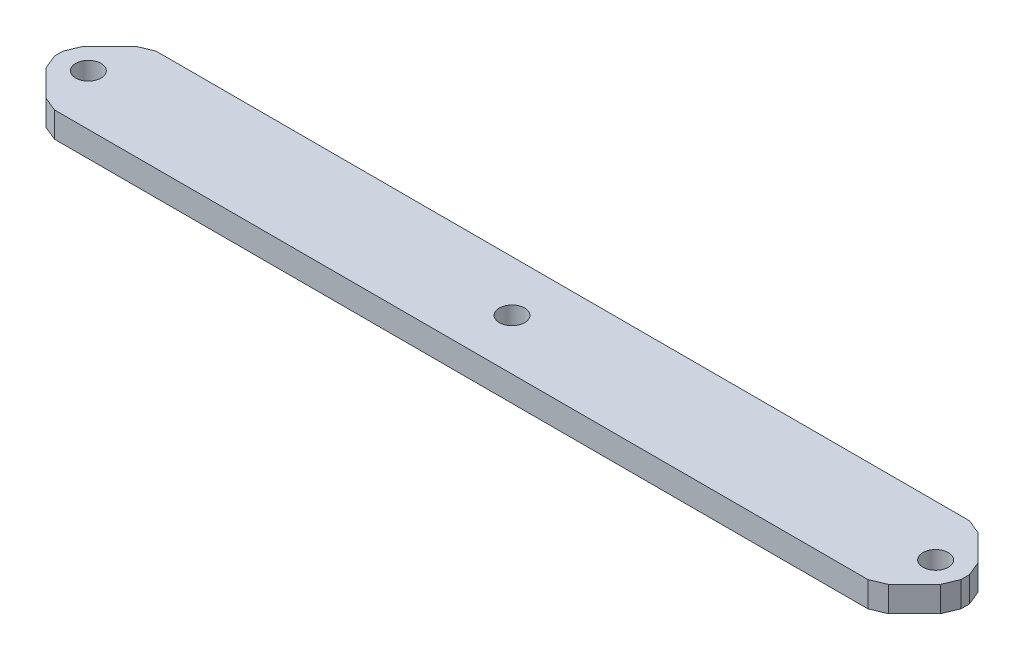
SolidWorks part; units mm, degrees
ref_plane "Front Plane" through (0, 0, 0) normal (0, 0, 1) x (1, 0, 0)
ref_plane "Top Plane" through (0, 0, 0) normal (0, 1, 0) x (1, 0, 0)
ref_plane "Right Plane" through (0, 0, 0) normal (1, 0, 0) x (0, 0, -1)
sketch "Sketch1" plane through (0, 0, 0) normal (0, 1, 0) x (1, 0, 0)
  line L0 (-55, 3) -> (-52, 6)
  line L1 (-52, 6) -> (52, 6)
  line L2 (-55, 3) -> (-55, -3)
  line L3 (-52, -6) -> (52, -6)
  line L4 (55, 3) -> (55, -3)
  line L5 (-55, 6) -> (55, -6) construction
  line L6 (-55, -6) -> (55, 6) construction
  line L7 (-55, -3) -> (-52, -6)
  line L8 (52, 6) -> (55, 3)
  line L9 (52, -6) -> (55, -3)
  circle A0 centre (-50, 0) radius 1.5
  circle A1 centre (0, 0) radius 1.5
  circle A2 centre (50, 0) radius 1.5
  point P0 (0, 0)
  dimension "D3" = 3
  dimension "D1" = 110
  dimension "D2" = 12
  dimension "D4" = 5
  dimension "D10" = 5
extrude "Boss-Extrude1" add sketch "Sketch1" along normal blind 3 contours A0 | L8 L4 L9 L3 L7 L2 L0 L1 | A1 | A2
sketch "Sketch2" plane through (0, 3, 0) normal (0, 1, 0) x (1, 0, 0)
  line L0 (-53.5, 4.5) -> (-53.5, -4.5)
  line L1 (-55, 3) -> (-52, 6) construction
  line L2 (-55, -3) -> (-52, -6) construction
  line L3 (-53.5, -4.5) -> (-55, -3)
  line L4 (-55, -3) -> (-55, 3)
  line L5 (-55, 3) -> (-53.5, 4.5)
  line L6 (0, 0) -> (0, 9.9984) construction
  line L7 (53.5, -4.5) -> (55, -3)
  line L8 (55, -3) -> (55, 3)
  line L9 (55, 3) -> (53.5, 4.5)
  line L10 (53.5, 4.5) -> (53.5, -4.5)
extrude "Cut-Extrude1" cut sketch "Sketch2" against normal through all both and the other way through all
sketch "Sketch3" plane through (0, 3, 0) normal (0, 1, 0) x (1, 0, 0)
  line L0 (-53.5, 1.5) -> (-49, 6)
  line L1 (-53.5, 4.5) -> (-53.5, -4.5) construction
  line L2 (-52, 6) -> (52, 6) construction
  line L3 (-53.5, 1.5) -> (-53.5, 4.5)
  line L4 (-53.5, 4.5) -> (-52, 6)
  line L5 (-52, 6) -> (-49, 6)
  line L6 (0, 0) -> (-7.5431, 0) construction
  line L7 (-2.9544, 6.0226) -> (-23.5602, -21.0219) construction
  line L8 (0, 0) -> (0, 4.5) construction
  line L9 (-53.5, -1.5) -> (-53.5, -4.5)
  line L10 (-53.5, -4.5) -> (-52, -6)
  line L11 (-52, -6) -> (-49, -6)
  line L12 (-53.5, -1.5) -> (-49, -6)
  line L13 (53.5, 1.5) -> (53.5, 4.5)
  line L14 (52, 6) -> (49, 6)
  line L15 (53.5, 4.5) -> (52, 6)
  line L16 (53.5, 1.5) -> (49, 6)
  line L17 (52, -6) -> (49, -6)
  line L18 (53.5, -4.5) -> (52, -6)
  line L19 (53.5, -1.5) -> (53.5, -4.5)
  line L20 (53.5, -1.5) -> (49, -6)
  line M11 (-52, 6) -> (-53.5, 4.5)
  line M12 (-53.5, 4.5) -> (-53.5, -4.5)
  line M13 (-53.5, -4.5) -> (-52, -6)
  line M14 (-52, -6) -> (52, -6)
  line M18 (52, 6) -> (-52, 6)
  dimension "D1" = 3
extrude "Cut-Extrude2" cut sketch "Sketch3" against normal through all both and the other way through all contours L12 M12 M13 M14 | L0 M12 M18 M11 | L14 L16 L13 L15 | L20 L17 L18 L19
chamfer "Chamfer1" distance 1 8 edges at (49, 1.5, 6) (53.5, 1.5, 1.5) (53.5, 1.5, -1.5) (49, 1.5, -6) (-49, 1.5, -6) (-53.5, 1.5, -1.5) (-49, 1.5, 6) (-53.5, 1.5, 1.5)
